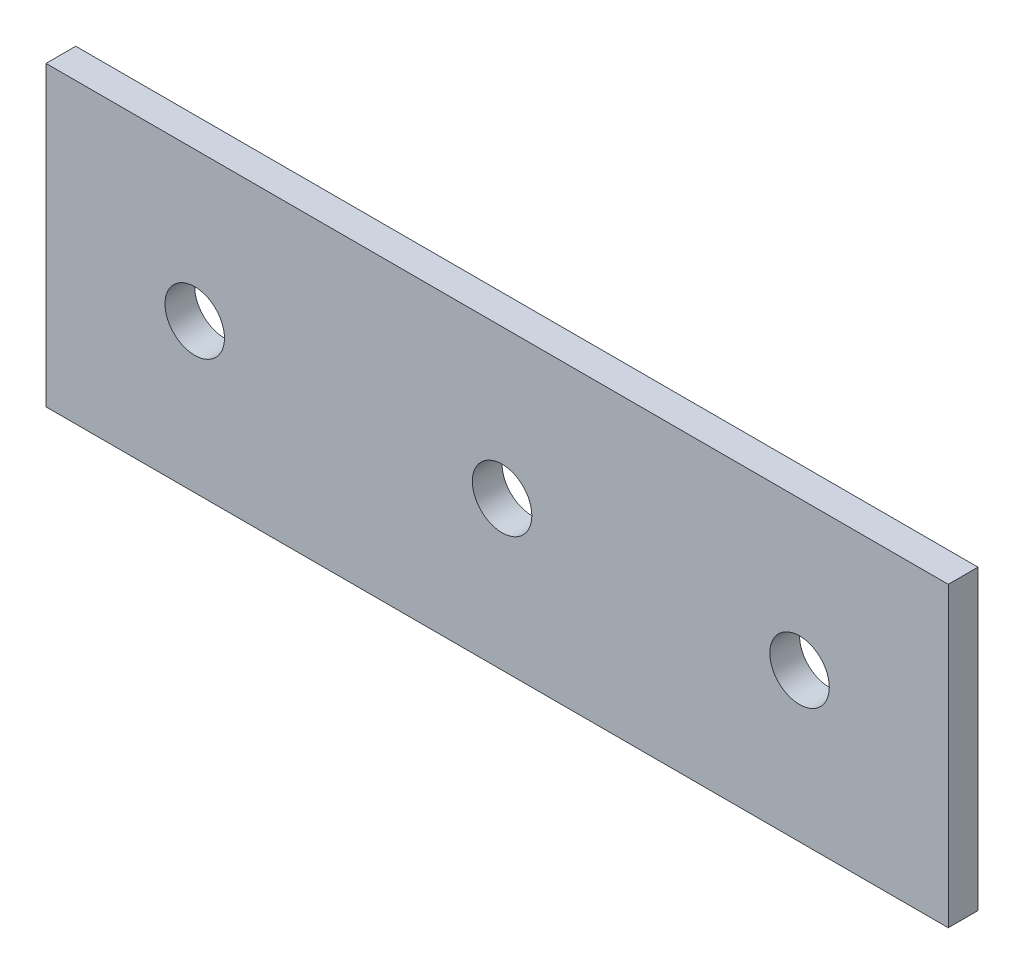
SolidWorks part; units mm, degrees
ref_plane "Plan de face" through (0, 0, 0) normal (0, 0, 1) x (1, 0, 0)
ref_plane "Plan de dessus" through (0, 0, 0) normal (0, 1, 0) x (1, 0, 0)
ref_plane "Plan de droite" through (0, 0, 0) normal (1, 0, 0) x (0, 0, -1)
sketch "Esquisse1" plane through (0, 0, 0) normal (0, 0, 1) x (1, 0, 0)
  line L0 (-36.0673, 7.4994) -> (9.4327, 7.4994) construction
  line L1 (-36.0673, 14.9994) -> (9.4327, 14.9994)
  line L2 (-36.0673, 14.9994) -> (-36.0673, -0.0006)
  line L3 (-36.0673, -0.0006) -> (9.4327, -0.0006)
  line L4 (9.4327, 14.9994) -> (9.4327, -0.0006)
  circle A0 centre (-28.5673, 7.4994) radius 1.5
  circle A1 centre (1.9327, 7.4994) radius 1.5
  circle A2 centre (-13.0673, 7.4994) radius 1.5
  dimension "D3" = 7.5
  dimension "D5" = 23
  dimension "D1" = 45.5
  dimension "D2" = 15
  dimension "D4" = 7.5
extrude "Extrusion1" add sketch "Esquisse1" along normal blind 1.5
